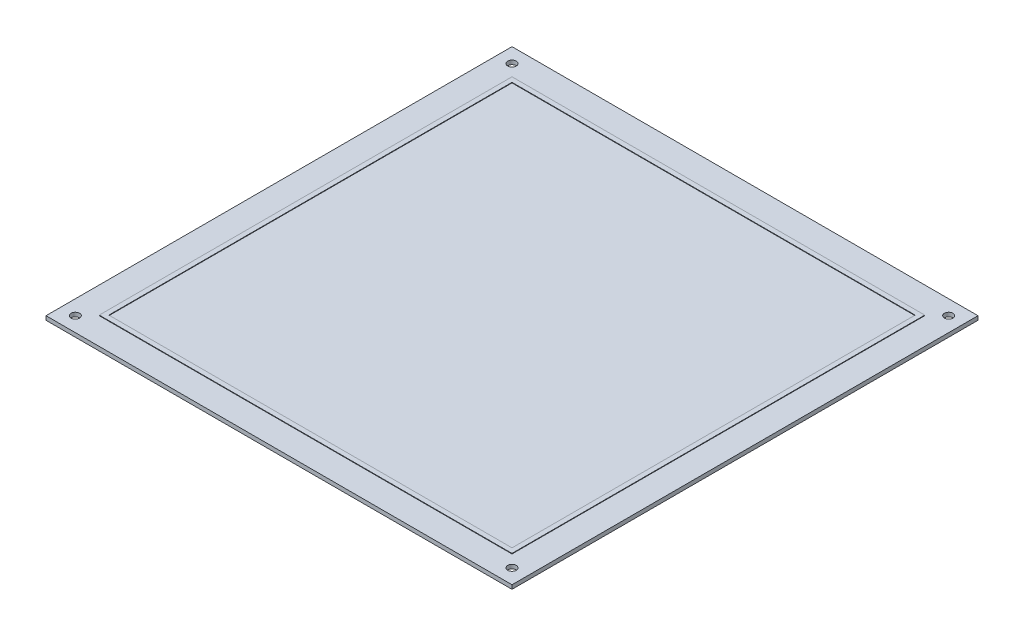
SolidWorks part; units mm, degrees
ref_plane "Front Plane" through (0, 0, 0) normal (0, 0, 1) x (1, 0, 0)
ref_plane "Top Plane" through (0, 0, 0) normal (0, 1, 0) x (1, 0, 0)
ref_plane "Right Plane" through (0, 0, 0) normal (1, 0, 0) x (0, 0, -1)
sketch "Sketch1" plane through (0, 0, 0) normal (0, 1, 0) x (1, 0, 0)
  line L1 (-175, -175) -> (175, -175)
  line L2 (-175, -175) -> (-175, 175)
  line L3 (-175, 175) -> (175, 175)
  line L4 (175, -175) -> (175, 175)
  circle A0 centre (164, 164) radius 3.2
  circle A1 centre (-164, 164) radius 3.2
  circle A2 centre (164, -164) radius 3.2
  circle A3 centre (-164, -164) radius 3.2
extrude "Base plate structural panel" add sketch "Sketch1" along normal mid plane 3
sketch "Sketch2" plane through (0, 0, 0) normal (0, 1, 0) x (1, 0, 0)
  line L1 (-155, -155) -> (155, -155)
  line L2 (-155, -155) -> (-155, 155)
  line L3 (-155, 155) -> (155, 155)
  line L4 (155, -155) -> (155, 155)
  line L5 (-151.4, -151.4) -> (151.4, -151.4)
  line L6 (-151.4, -151.4) -> (-151.4, 151.4)
  line L7 (-151.4, 151.4) -> (151.4, 151.4)
  line L8 (151.4, -151.4) -> (151.4, 151.4)
extrude "Base plate structural panel inset stiffener" add sketch "Sketch2" along normal mid plane 3.8
sketch "Sketch3" plane through (0, 0, 0) normal (0, 1, 0) x (1, 0, 0)
  circle A0 centre (164, 164) radius 3.2
  circle A1 centre (-164, 164) radius 3.2
  circle A2 centre (164, -164) radius 3.2
  circle A3 centre (-164, -164) radius 3.2
